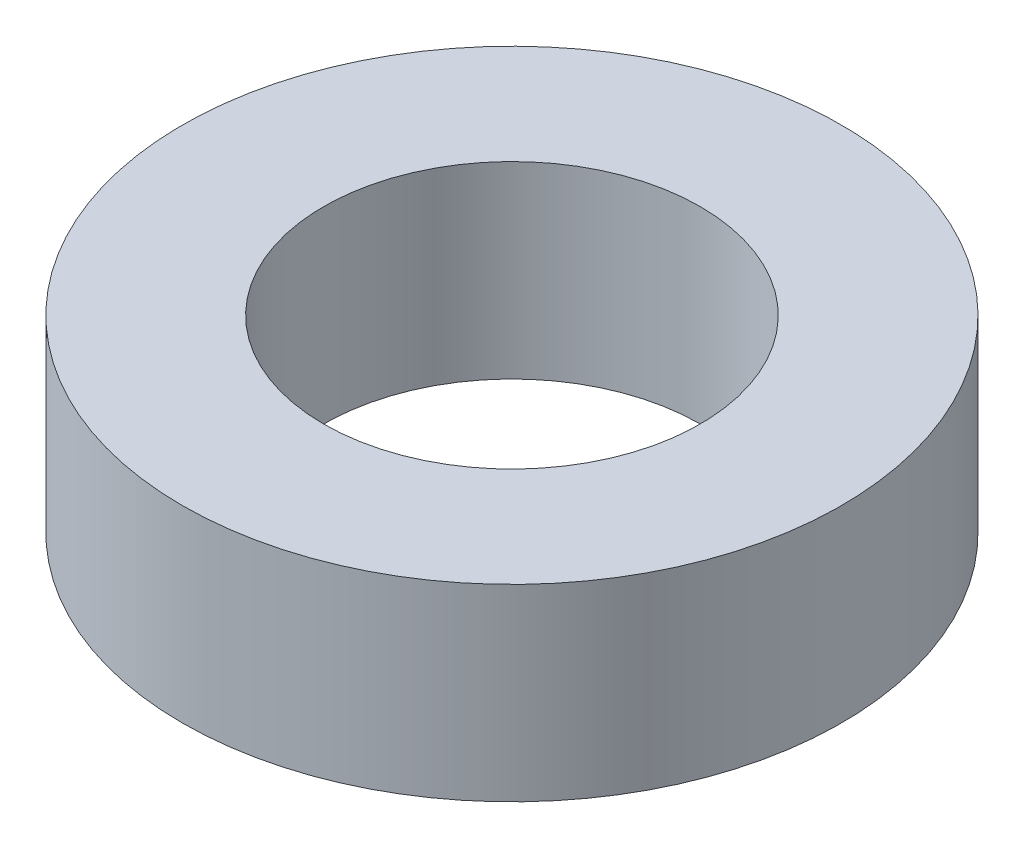
SolidWorks part; units mm, degrees
ref_plane "Ebene vorne" through (0, 0, 0) normal (0, 0, 1) x (1, 0, 0)
ref_plane "Ebene oben" through (0, 0, 0) normal (0, 1, 0) x (1, 0, 0)
ref_plane "Ebene rechts" through (0, 0, 0) normal (1, 0, 0) x (0, 0, -1)
sketch "Skizze1" plane through (0, 0, 0) normal (0, 1, 0) x (1, 0, 0)
  circle A0 centre (0, 0) radius 7
  dimension "D1" = 14
extrude "Aufsatz-Linear austragen1" add sketch "Skizze1" along normal blind 4
sketch "Skizze2" plane through (0, 4, 0) normal (0, 1, 0) x (1, 0, 0)
  circle A0 centre (0, 0) radius 4
  dimension "D1" = 8
extrude "Schnitt-Linear austragen1" cut sketch "Skizze2" against normal blind 4
